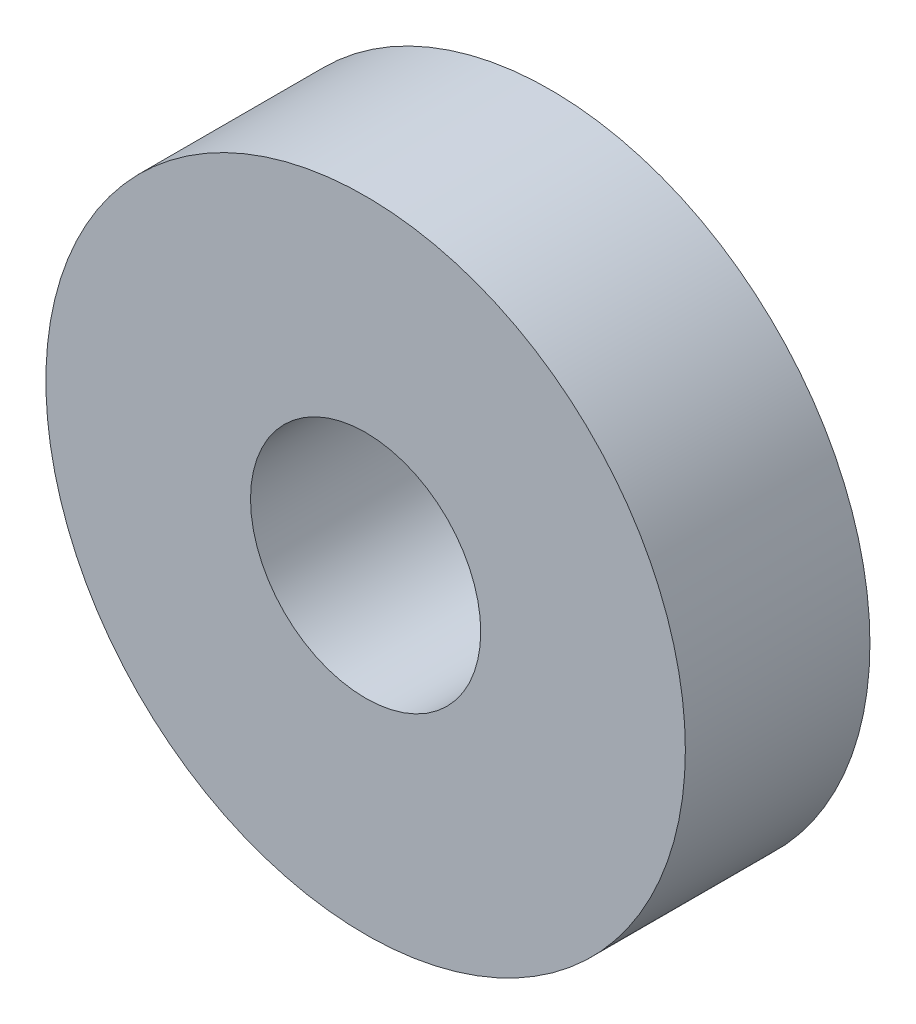
SolidWorks part; units mm, degrees
ref_plane "Plan de face" through (0, 0, 0) normal (0, 0, 1) x (1, 0, 0)
ref_plane "Plan de dessus" through (0, 0, 0) normal (0, 1, 0) x (1, 0, 0)
ref_plane "Plan de droite" through (0, 0, 0) normal (1, 0, 0) x (0, 0, -1)
sketch "Esquisse1" plane through (0, 0, 0) normal (0, 0, 1) x (1, 0, 0)
  circle A0 centre (0, 0) radius 11
  circle A1 centre (0, 0) radius 3.96
  dimension "D1" = 22
  dimension "D2" = 7.92
extrude "Boss.-Extru.1" add sketch "Esquisse1" along normal blind 6.35
